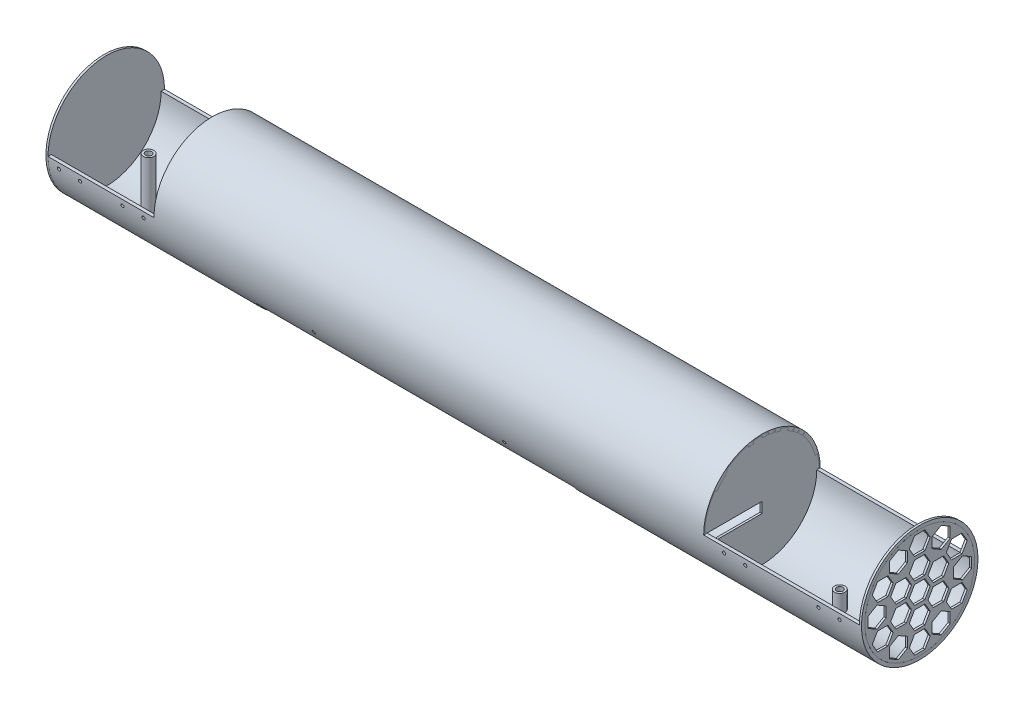
SolidWorks part; units mm, degrees
other "标注1"
sketch "草图27" plane through (-2, 77.9653, 55) normal (0, 1, 0) x (-1, 0, 0)
ref_plane "前视基准面" through (0, 0, 0) normal (0, 0, 1) x (1, 0, 0)
ref_plane "上视基准面" through (0, 0, 0) normal (0, 1, 0) x (1, 0, 0)
ref_plane "右视基准面" through (0, 0, 0) normal (1, 0, 0) x (0, 0, -1)
sketch "草图2" plane through (0, 0, 0) normal (1, 0, 0) x (0, 0, -1)
  circle A0 centre (0, 0) radius 55
  circle A1 centre (0, 0) radius 51.8
  dimension "D1" = 110
  dimension "D2" = 103.6
extrude "凸台-拉伸1" add sketch "草图2" along normal blind 768
ref_plane "基准面4" through (100, 0, 0) normal (1, 0, 0) x (0, 0, -1)
sketch "草图3" plane through (100, 0, 0) normal (1, 0, 0) x (0, 0, -1)
  circle A0 centre (0, 0) radius 54
  dimension "D1" = 108
extrude "凸台-拉伸2" add sketch "草图3" along normal blind 2 separate body
ref_plane "基准面5" through (400, 0, 0) normal (1, 0, 0) x (0, 0, -1)
ref_plane "基准面6" through (565, 0, 0) normal (1, 0, 0) x (0, 0, -1)
sketch "草图7" plane through (0, 0, 0) normal (1, 0, 0) x (0, 0, -1)
  circle A1 centre (0, 0) radius 55
extrude "凸台-拉伸5" add sketch "草图7" against normal blind 2 separate body
ref_plane "基准面7" through (102, 0, 0) normal (1, 0, 0) x (0, 0, -1)
ref_plane "基准面8" through (450, 0, 0) normal (1, 0, 0) x (0, 0, -1)
sketch "草图8" plane through (450, 0, 0) normal (1, 0, 0) x (0, 0, -1)
  circle A0 centre (0, 0) radius 53
ref_plane "基准面9" through (507.5, 0, 0) normal (1, 0, 0) x (0, 0, -1)
ref_plane "基准面10" through (615, 0, 0) normal (1, 0, 0) x (0, 0, -1)
sketch "草图9" plane through (615, 0, 0) normal (1, 0, 0) x (0, 0, -1)
  circle A0 centre (0, 0) radius 53
sketch "草图12" plane through (0, 0, 0) normal (0, 0, 1) x (1, 0, 0)
  line L0 (615, 0) -> (565, 0)
  line L1 (615, -60.5) -> (615, 60.5) construction
  line L2 (768, 0) -> (0, 0) construction
  line L3 (565, -60.5) -> (565, 60.5) construction
sketch "草图14" plane through (0, 0, 0) normal (0, 1, 0) x (1, 0, 0)
  line L1 (619, 55) -> (766, 55)
  line L3 (619, 0) -> (766, 0)
  line L4 (766, 55) -> (766, 0)
  line L5 (768, -55) -> (768, 55) construction
  line L9 (619, 55) -> (619, 0)
  dimension "D1" = 2
  dimension "D3" = 147
ref_plane "基准面11" through (617, 0, 0) normal (1, 0, 0) x (0, 0, -1)
sketch "草图15" plane through (617, 0, 0) normal (1, 0, 0) x (0, 0, -1)
  circle A0 centre (0, 0) radius 53
revolve "切除-旋转1" cut sketch "草图14" angle 180 about L3
sketch "草图16" plane through (0, 0, 0) normal (0, 1, 0) x (1, 0, 0)
  line L0 (100, -60.5) -> (100, 60.5) construction
  line L1 (0, 0) -> (100, 0)
  line L2 (0, 0) -> (0, 55)
  line L3 (0, 55) -> (100, 55)
  line L4 (100, 0) -> (100, 55)
  line L5 (619, 55) -> (0, 55) construction
  dimension "D1" = 100
  dimension "D2" = 55
revolve "切除-旋转2" cut sketch "草图16" angle 180 about L1
ref_plane "基准面12" through (435, 0, 0) normal (1, 0, 0) x (0, 0, -1)
sketch "草图17" plane through (435, 0, 0) normal (1, 0, 0) x (0, 0, -1)
  line L0 (0, 77.9653) -> (0, -80.6413) construction
  circle A0 centre (0, -67) radius 12
  circle A1 centre (0, -67) radius 10
  circle A2 centre (0, 0) radius 55 construction
  dimension "D1" = 24
  dimension "D2" = 20
ref_plane "基准面13" through (200, 0, 0) normal (1, 0, 0) x (0, 0, -1)
ref_plane "基准面14" through (0, 0, -50) normal (0, 0, 1) x (1, 0, 0)
sketch "草图19" plane through (0, 0, -50) normal (0, 0, 1) x (1, 0, 0)
  line L0 (766, 0) -> (619, 0) construction
  line L1 (766, 55) -> (766, 0) construction
  line L2 (619, 0) -> (619, 51.8) construction
  circle A0 centre (743, -5.4) radius 1.5
  circle A1 centre (723, -5.4) radius 1.5
  circle A2 centre (662, -5.4) radius 1.5
  circle A3 centre (642, -5.4) radius 1.5
  dimension "D1" = 3
  dimension "D2" = 3
  dimension "D6" = 3
  dimension "D7" = 3
  dimension "D3" = 20
  dimension "D4" = 5.4
  dimension "D5" = 23
  dimension "D8" = 20
  dimension "D9" = 5.4
  dimension "D10" = 23
  dimension "D11" = 5.4
sketch "草图22" plane through (0, 0, -50) normal (0, 0, 1) x (1, 0, 0)
  line L0 (0, 0) -> (0, -55) construction
  line L1 (100, 55) -> (100, 0) construction
  line L2 (100, 0) -> (0, 0) construction
  circle A0 centre (10, -5.4) radius 1.5
  circle A1 centre (30, -5.4) radius 1.5
  circle A2 centre (70, -5.4) radius 1.5
  circle A3 centre (90, -5.4) radius 1.5
  dimension "D1" = 3
  dimension "D2" = 3
  dimension "D7" = 3
  dimension "D8" = 3
  dimension "D3" = 10
  dimension "D4" = 20
  dimension "D5" = 20
  dimension "D6" = 10
  dimension "D9" = 5.4
extrude "切除-拉伸4" cut sketch "草图22" along normal through all
ref_plane "基准面16" through (597, 0, 0) normal (1, 0, 0) x (0, 0, -1)
sketch "草图23" plane through (597, 0, 0) normal (1, 0, 0) x (0, 0, -1)
  circle A0 centre (0, 0) radius 53
sketch "草图24" plane through (0, 0, -50) normal (0, 0, 1) x (1, 0, 0)
  line L0 (766, 0) -> (619, 0) construction
  line L1 (619, 0) -> (619, 55) construction
  line L2 (766, 55) -> (766, 0) construction
  circle A0 centre (638, -5.4) radius 1.5
  circle A1 centre (658, -5.4) radius 1.5
  circle A2 centre (727, -5.4) radius 1.5
  circle A3 centre (747, -5.4) radius 1.5
  dimension "D3" = 3
  dimension "D4" = 3
  dimension "D6" = 3
  dimension "D7" = 3
  dimension "D1" = 20
  dimension "D2" = 5.4
  dimension "D5" = 20
  dimension "D8" = 5.4
  dimension "D9" = 19
  dimension "D10" = 19
extrude "切除-拉伸5" cut sketch "草图24" along normal through all
ref_plane "基准面17" through (222.4934, 0, 0) normal (1, 0, 0) x (0, 0, -1)
sketch "草图25" plane through (222.4934, 0, 0) normal (1, 0, 0) x (0, 0, -1)
  circle A0 centre (0, -67) radius 12
  circle A1 centre (0, -67) radius 10
  circle A2 centre (0, 0) radius 55 construction
  dimension "D1" = 24
  dimension "D2" = 20
ref_plane "基准面18" through (0, 0, 0) normal (1, 0, 0) x (0, 0, -1)
ref_plane "基准面19" through (470, 0, 0) normal (1, 0, 0) x (0, 0, -1)
ref_plane "基准面20" through (718, 0, 0) normal (1, 0, 0) x (0, 0, -1)
sketch "草图28" plane through (718, 0, 0) normal (1, 0, 0) x (0, 0, -1)
  circle A0 centre (0, 0) radius 51.8
  dimension "D1" = 103.6
extrude "凸台-拉伸16" add sketch "草图28" along normal blind 50 separate body
ref_plane "基准面21" through (619, 0, 0) normal (1, 0, 0) x (0, 0, -1)
sketch "草图29" plane through (619, 0, 0) normal (1, 0, 0) x (0, 0, -1)
  circle A0 centre (0, 0) radius 54
  dimension "D1" = 108
extrude "凸台-拉伸17" add sketch "草图29" against normal blind 2 separate body
sketch "草图30" plane through (0, 0, 0) normal (0, 0, 1) x (1, 0, 0)
  line L3 (233.5, 0) -> (533.5, 0)
  line L6 (0, -55) -> (768, -55) construction
  line L7 (233.5, 0) -> (533.5, 0)
  line L8 (233.5, 0) -> (233.5, -55)
  line L9 (233.5, -55) -> (533.5, -55)
  line L10 (533.5, 0) -> (533.5, -55)
  line L11 (619, 0) -> (619, 55) construction
  dimension "D1" = 300
  dimension "D2" = 55
  dimension "D3" = 85.5
sketch "草图31" plane through (619, 0, 0) normal (1, 0, 0) x (0, 0, -1)
  line L0 (-52.8334, 0) -> (0, 0)
  line L1 (0, 0) -> (0, -10)
  line L2 (0, -10) -> (-51.8784, -10)
  arc A0 (-52.8334, 0) -> (-51.8784, -10) centre (0, 0) ccw
  dimension "D1" = 10
extrude "切除-拉伸6" cut sketch "草图31" against normal blind 536
sketch "草图32" plane through (0, 0, 0) normal (0, 0, 1) x (1, 0, 0)
  line L0 (0, -55) -> (768, -55) construction
  line L1 (185.5, 0) -> (485.5, 0)
  line L2 (185.5, 0) -> (185.5, -55)
  line L3 (185.5, -55) -> (485.5, -55)
  line L4 (485.5, 0) -> (485.5, -55)
  line L5 (100, 55) -> (100, 0) construction
  dimension "D1" = 300
  dimension "D2" = 55
  dimension "D3" = 85.5
revolve "切除-旋转4" cut sketch "草图32" angle 54 about axis through (768, 0, 0) along (-1, 0, 0) other way angle 54
sketch "草图35" plane through (718, 0, 0) normal (-1, 0, 0) x (0, 0, 1)
  line L0 (0, 0) -> (-41.9071, -30.4473)
  line L1 (0, 0) -> (41.9071, -30.4473)
  line L2 (0, 0) -> (0, -51.8) construction
  circle A0 centre (0, 0) radius 51.8 construction
  arc A1 (-41.9071, -30.4473) -> (41.9071, -30.4473) centre (0, 0) ccw
  dimension "D1" = 108
ref_plane "基准面22" through (0, 0, 45) normal (0, 0, 1) x (1, 0, 0)
sketch "草图36" plane through (0, 0, 45) normal (0, 0, 1) x (1, 0, 0)
  line L0 (185.5, -32.3282) -> (485.5, -32.3282) construction
  line L1 (485.5, -32.3282) -> (485.5, -55) construction
  line L2 (185.5, -55) -> (185.5, -32.3282) construction
  circle A0 centre (425.5, -23.4722) radius 1.5
  circle A1 centre (245.5, -23.4722) radius 1.5
  dimension "D3" = 3
  dimension "D5" = 3
  dimension "D1" = 8.856
  dimension "D2" = 60
  dimension "D4" = 60
extrude "切除-拉伸7" cut sketch "草图36" against normal through all both and the other way through all
sketch "草图37" plane through (0, 0, 0) normal (0, 1, 0) x (1, 0, 0)
  line L1 (0, -55) -> (0, 55) construction
  circle A0 centre (40, 0) radius 5
  circle A1 centre (40, 0) radius 3
  dimension "D1" = 10
  dimension "D2" = 6
  dimension "D3" = 40
extrude "凸台-拉伸19" add sketch "草图37" against normal up to body
sketch "草图39" plane through (0, 0, 0) normal (0, 1, 0) x (1, 0, 0)
  line L1 (766, 51.8) -> (766, -51.8) construction
  line L2 (766, 55) -> (766, -55) construction
  circle A0 centre (692.5, 0) radius 5
  circle A1 centre (692.5, 0) radius 3
  point P9 (766, 0)
  dimension "D1" = 10
  dimension "D2" = 6
  dimension "D3" = 73.5
extrude "凸台-拉伸21" add sketch "草图39" against normal up to body
sketch "草图40" plane through (0, 0, 0) normal (0, 1, 0) x (1, 0, 0)
  circle A0 centre (40, 0) radius 3 construction
  circle A1 centre (40, 0) radius 5
  circle A2 centre (40, 0) radius 5
  circle A3 centre (40, 0) radius 3
  dimension "D1" = 0
extrude "切除-拉伸8" cut sketch "草图40" against normal blind 5
sketch "草图41" plane through (0, 0, 0) normal (0, 1, 0) x (1, 0, 0)
  circle A1 centre (692.5, 0) radius 3 construction
  circle A2 centre (692.5, 0) radius 5
  circle A3 centre (692.5, 0) radius 5
  circle A4 centre (692.5, 0) radius 3
  dimension "D1" = 0
extrude "切除-拉伸9" cut sketch "草图41" against normal blind 35
ref_plane "基准面23" through (0, 0, -52.0375) normal (0, 0, 1) x (1, 0, 0)
sketch "草图42" plane through (0, 0, -52.0375) normal (0, 0, 1) x (1, 0, 0)
  line L0 (766, 0) -> (619, 0) construction
  line L1 (766, 55) -> (766, 0) construction
  circle A0 centre (761, -5) radius 1.5
  dimension "D1" = 3
  dimension "D2" = 5
  dimension "D3" = 5
extrude "切除-拉伸10" cut sketch "草图42" against normal blind 44
sketch "草图44" plane through (718, 0, 0) normal (-1, 0, 0) x (0, 0, 1)
  line L0 (0, 40.3627) -> (0, 0) construction
  line L1 (4.9412, 48.8975) -> (-4.9208, 48.9093)
  line L2 (-4.9208, 48.9093) -> (-9.8619, 40.3745)
  line L3 (-9.8619, 40.3745) -> (-4.9412, 31.8279)
  line L4 (-4.9412, 31.8279) -> (4.9208, 31.8161)
  line L5 (4.9208, 31.8161) -> (9.8619, 40.3509)
  line L6 (9.8619, 40.3509) -> (4.9412, 48.8975)
  line L7 (4.9412, 28.8975) -> (-4.9208, 28.9093)
  line L8 (-4.9208, 28.9093) -> (-9.8619, 20.3745)
  line L9 (-9.8619, 20.3745) -> (-4.9412, 11.8279)
  line L10 (-4.9412, 11.8279) -> (4.9208, 11.8161)
  line L11 (4.9208, 11.8161) -> (9.8619, 20.3509)
  line L12 (9.8619, 20.3509) -> (4.9412, 28.8975)
  line L13 (4.9412, 8.8975) -> (-4.9208, 8.9093)
  line L14 (-4.9208, 8.9093) -> (-9.8619, 0.3745)
  line L15 (-9.8619, 0.3745) -> (-4.9412, -8.1721)
  line L16 (-4.9412, -8.1721) -> (4.9208, -8.1839)
  line L17 (4.9208, -8.1839) -> (9.8619, 0.3509)
  line L18 (9.8619, 0.3509) -> (4.9412, 8.8975)
  line L31 (28.728, 39.8759) -> (20.1932, 44.8171)
  line L32 (20.1932, 44.8171) -> (11.6466, 39.8963)
  line L33 (11.6466, 39.8963) -> (11.6348, 30.0344)
  line L34 (11.6348, 30.0344) -> (20.1696, 25.0932)
  line L35 (20.1696, 25.0932) -> (28.7162, 30.0139)
  line L36 (28.7162, 30.0139) -> (28.728, 39.8759)
  line L37 (44.8171, 20.1696) -> (39.8963, 28.7162)
  line L38 (39.8963, 28.7162) -> (30.0344, 28.728)
  line L39 (30.0344, 28.728) -> (25.0932, 20.1932)
  line L40 (25.0932, 20.1932) -> (30.0139, 11.6466)
  line L41 (30.0139, 11.6466) -> (39.8759, 11.6348)
  line L42 (39.8759, 11.6348) -> (44.8171, 20.1696)
  line L43 (48.8975, -4.9412) -> (48.9093, 4.9208)
  line L44 (48.9093, 4.9208) -> (40.3745, 9.8619)
  line L45 (40.3745, 9.8619) -> (31.8279, 4.9412)
  line L46 (31.8279, 4.9412) -> (31.8161, -4.9208)
  line L47 (31.8161, -4.9208) -> (40.3509, -9.8619)
  line L48 (40.3509, -9.8619) -> (48.8975, -4.9412)
  line L49 (39.8759, -28.728) -> (44.8171, -20.1932)
  line L50 (44.8171, -20.1932) -> (39.8963, -11.6466)
  line L51 (39.8963, -11.6466) -> (30.0344, -11.6348)
  line L52 (30.0344, -11.6348) -> (25.0932, -20.1696)
  line L53 (25.0932, -20.1696) -> (30.0139, -28.7162)
  line L54 (30.0139, -28.7162) -> (39.8759, -28.728)
  line L55 (20.1696, -44.8171) -> (28.7162, -39.8963)
  line L56 (28.7162, -39.8963) -> (28.728, -30.0344)
  line L57 (28.728, -30.0344) -> (20.1932, -25.0932)
  line L58 (20.1932, -25.0932) -> (11.6466, -30.0139)
  line L59 (11.6466, -30.0139) -> (11.6348, -39.8759)
  line L60 (11.6348, -39.8759) -> (20.1696, -44.8171)
  line L61 (-4.9412, -48.8975) -> (4.9208, -48.9093)
  line L62 (4.9208, -48.9093) -> (9.8619, -40.3745)
  line L63 (9.8619, -40.3745) -> (4.9412, -31.8279)
  line L64 (4.9412, -31.8279) -> (-4.9208, -31.8161)
  line L65 (-4.9208, -31.8161) -> (-9.8619, -40.3509)
  line L66 (-9.8619, -40.3509) -> (-4.9412, -48.8975)
  line L67 (-28.728, -39.8759) -> (-20.1932, -44.8171)
  line L68 (-20.1932, -44.8171) -> (-11.6466, -39.8963)
  line L69 (-11.6466, -39.8963) -> (-11.6348, -30.0344)
  line L70 (-11.6348, -30.0344) -> (-20.1696, -25.0932)
  line L71 (-20.1696, -25.0932) -> (-28.7162, -30.0139)
  line L72 (-28.7162, -30.0139) -> (-28.728, -39.8759)
  line L73 (-44.8171, -20.1696) -> (-39.8963, -28.7162)
  line L74 (-39.8963, -28.7162) -> (-30.0344, -28.728)
  line L75 (-30.0344, -28.728) -> (-25.0932, -20.1932)
  line L76 (-25.0932, -20.1932) -> (-30.0139, -11.6466)
  line L77 (-30.0139, -11.6466) -> (-39.8759, -11.6348)
  line L78 (-39.8759, -11.6348) -> (-44.8171, -20.1696)
  line L79 (-48.8975, 4.9412) -> (-48.9093, -4.9208)
  line L80 (-48.9093, -4.9208) -> (-40.3745, -9.8619)
  line L81 (-40.3745, -9.8619) -> (-31.8279, -4.9412)
  line L82 (-31.8279, -4.9412) -> (-31.8161, 4.9208)
  line L83 (-31.8161, 4.9208) -> (-40.3509, 9.8619)
  line L84 (-40.3509, 9.8619) -> (-48.8975, 4.9412)
  line L85 (-39.8759, 28.728) -> (-44.8171, 20.1932)
  line L86 (-44.8171, 20.1932) -> (-39.8963, 11.6466)
  line L87 (-39.8963, 11.6466) -> (-30.0344, 11.6348)
  line L88 (-30.0344, 11.6348) -> (-25.0932, 20.1696)
  line L89 (-25.0932, 20.1696) -> (-30.0139, 28.7162)
  line L90 (-30.0139, 28.7162) -> (-39.8759, 28.728)
  line L91 (-20.1696, 44.8171) -> (-28.7162, 39.8963)
  line L92 (-28.7162, 39.8963) -> (-28.728, 30.0344)
  line L93 (-28.728, 30.0344) -> (-20.1932, 25.0932)
  line L94 (-20.1932, 25.0932) -> (-11.6466, 30.0139)
  line L95 (-11.6466, 30.0139) -> (-11.6348, 39.8759)
  line L96 (-11.6348, 39.8759) -> (-20.1696, 44.8171)
  line L97 (27.4966, 10.1696) -> (22.5758, 18.7162)
  line L98 (22.5758, 18.7162) -> (12.7139, 18.728)
  line L99 (12.7139, 18.728) -> (7.7727, 10.1932)
  line L100 (7.7727, 10.1932) -> (12.6934, 1.6466)
  line L101 (12.6934, 1.6466) -> (22.5554, 1.6348)
  line L102 (22.5554, 1.6348) -> (27.4966, 10.1696)
  line L103 (22.5554, -18.728) -> (27.4966, -10.1932)
  line L104 (27.4966, -10.1932) -> (22.5758, -1.6466)
  line L105 (22.5758, -1.6466) -> (12.7139, -1.6348)
  line L106 (12.7139, -1.6348) -> (7.7727, -10.1696)
  line L107 (7.7727, -10.1696) -> (12.6934, -18.7162)
  line L108 (12.6934, -18.7162) -> (22.5554, -18.728)
  line L109 (-4.9412, -28.8975) -> (4.9208, -28.9093)
  line L110 (4.9208, -28.9093) -> (9.8619, -20.3745)
  line L111 (9.8619, -20.3745) -> (4.9412, -11.8279)
  line L112 (4.9412, -11.8279) -> (-4.9208, -11.8161)
  line L113 (-4.9208, -11.8161) -> (-9.8619, -20.3509)
  line L114 (-9.8619, -20.3509) -> (-4.9412, -28.8975)
  line L115 (-27.4966, -10.1696) -> (-22.5758, -18.7162)
  line L116 (-22.5758, -18.7162) -> (-12.7139, -18.728)
  line L117 (-12.7139, -18.728) -> (-7.7727, -10.1932)
  line L118 (-7.7727, -10.1932) -> (-12.6934, -1.6466)
  line L119 (-12.6934, -1.6466) -> (-22.5554, -1.6348)
  line L120 (-22.5554, -1.6348) -> (-27.4966, -10.1696)
  line L121 (-22.5554, 18.728) -> (-27.4966, 10.1932)
  line L122 (-27.4966, 10.1932) -> (-22.5758, 1.6466)
  line L123 (-22.5758, 1.6466) -> (-12.7139, 1.6348)
  line L124 (-12.7139, 1.6348) -> (-7.7727, 10.1696)
  line L125 (-7.7727, 10.1696) -> (-12.6934, 18.7162)
  line L126 (-12.6934, 18.7162) -> (-22.5554, 18.728)
  line L127 (4.9412, -11.1025) -> (-4.9208, -11.0907) [skipped]
  line L128 (-4.9208, -11.0907) -> (-9.8619, -19.6255) [skipped]
  line L129 (-9.8619, -19.6255) -> (-4.9412, -28.1721) [skipped]
  line L130 (-4.9412, -28.1721) -> (4.9208, -28.1839) [skipped]
  line L131 (4.9208, -28.1839) -> (9.8619, -19.6491) [skipped]
  line L132 (9.8619, -19.6491) -> (4.9412, -11.1025) [skipped]
  line L133 (4.9412, -31.1025) -> (-4.9208, -31.0907) [skipped]
  line L134 (-4.9208, -31.0907) -> (-9.8619, -39.6255) [skipped]
  line L135 (-9.8619, -39.6255) -> (-4.9412, -48.1721) [skipped]
  line L136 (-4.9412, -48.1721) -> (4.9208, -48.1839) [skipped]
  line L137 (4.9208, -48.1839) -> (9.8619, -39.6491) [skipped]
  line L138 (9.8619, -39.6491) -> (4.9412, -31.1025) [skipped]
  circle A0 centre (0, 40.3627) radius 8.5407 construction
  point P102 (0, 0)
  point P133 (0, 0)
  dimension "D1" = 5
  dimension "D2" = 12
  dimension "D3" = 6
extrude "切除-拉伸12" cut sketch "草图44" against normal through all
sketch "草图45" plane through (718, 0, 0) normal (-1, 0, 0) x (0, 0, 1)
  circle A0 centre (0, 0) radius 51.8
  dimension "D1" = 103.6
extrude "切除-拉伸13" cut sketch "草图45" against normal blind 48
